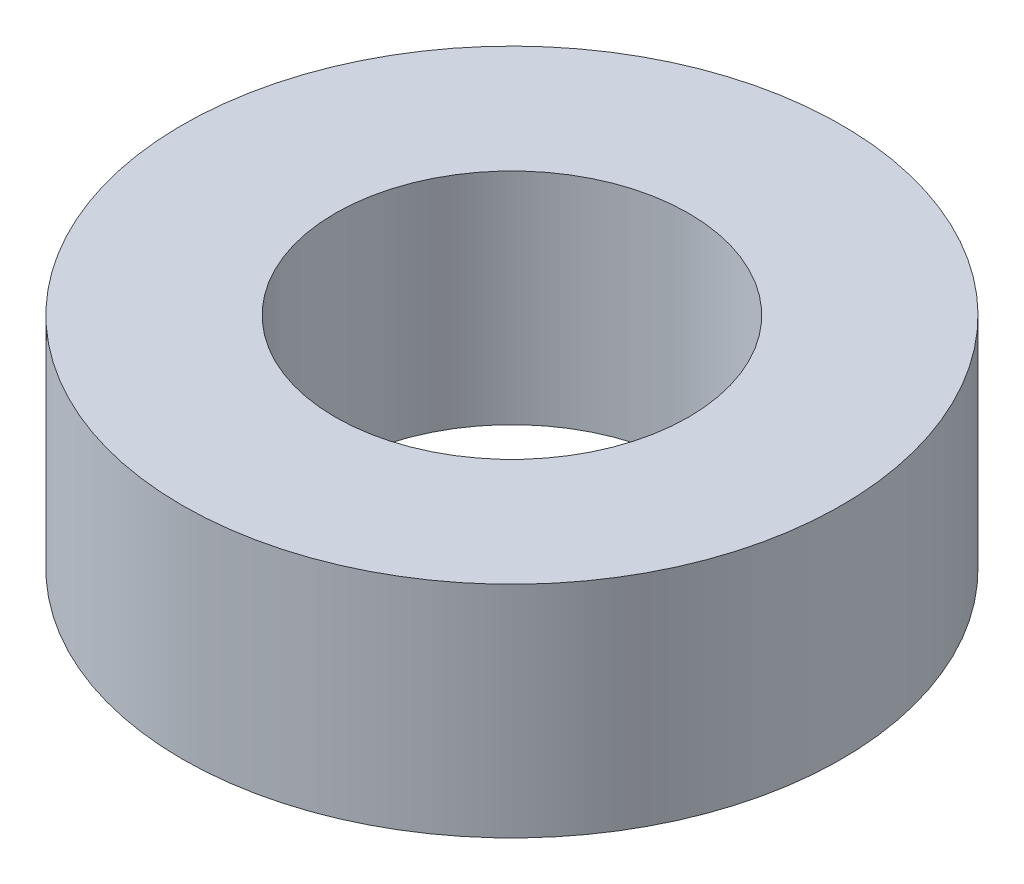
SolidWorks part; units mm, degrees
material "Nylon 101"
ref_plane "Front Plane" through (0, 0, 0) normal (0, 0, 1) x (1, 0, 0)
ref_plane "Top Plane" through (0, 0, 0) normal (0, 1, 0) x (1, 0, 0)
ref_plane "Right Plane" through (0, 0, 0) normal (1, 0, 0) x (0, 0, -1)
sketch "Sketch1" plane through (0, 0, 0) normal (0, 1, 0) x (1, 0, 0)
  circle A0 centre (0, 0) radius 2.5527
  circle A1 centre (0, 0) radius 4.7625
  dimension "D1" = 5.1054
  dimension "D2" = 9.525
extrude "Boss-Extrude1" add sketch "Sketch1" along normal mid plane 3.175
sketch "Sketch2" plane through (0, 1.5875, 0) normal (0, 1, 0) x (1, 0, 0)
  line L0 (-1.9715, 2.794) -> (3.166, 2.794) construction
  circle A0 centre (0, 0) radius 2.5527 construction
  text T0 "5001" font "Consolas" height 1.1906
  dimension "D1" = 2.794
extrude "Cut-Extrude1" [suppressed] cut sketch "Sketch2" against normal blind 0.2
